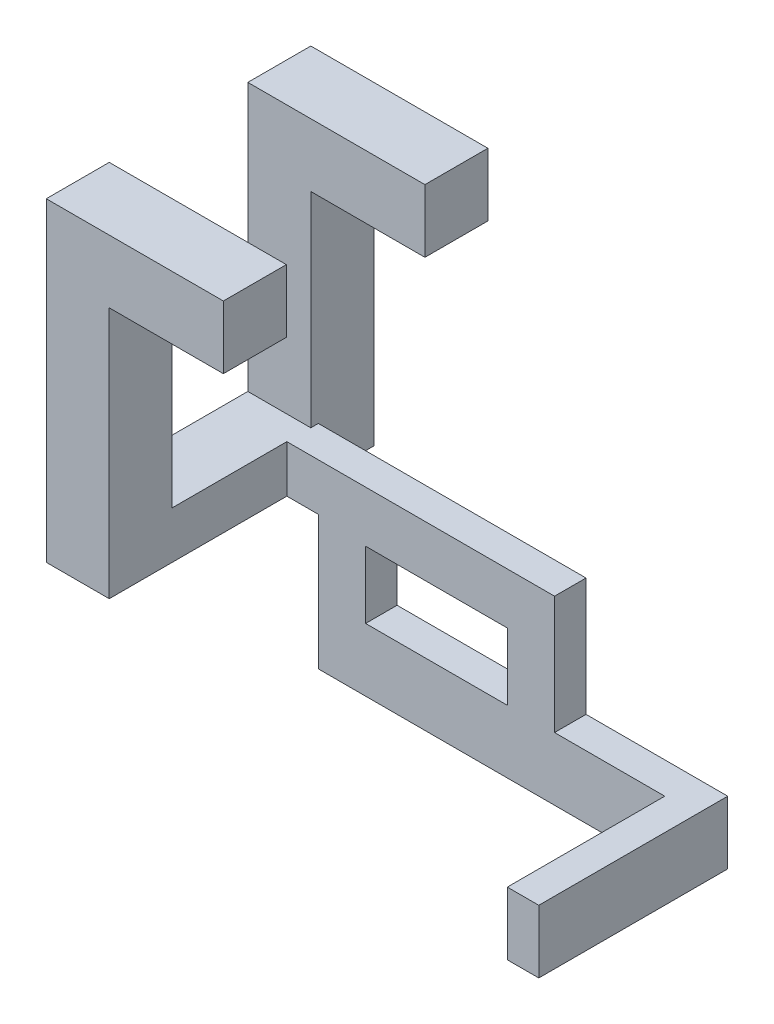
SolidWorks part; units mm, degrees
ref_plane "Front Plane" through (0, 0, 0) normal (0, 0, 1) x (1, 0, 0)
ref_plane "Top Plane" through (0, 0, 0) normal (0, 1, 0) x (1, 0, 0)
ref_plane "Right Plane" through (0, 0, 0) normal (1, 0, 0) x (0, 0, -1)
sketch "Sketch2" plane through (0, 0, 0) normal (0, 0, 1) x (1, 0, 0)
  line L1 (19.05, -14.605) -> (-19.05, -14.605)
  line L2 (19.05, -14.605) -> (19.05, 14.605)
  line L3 (19.05, 14.605) -> (-19.05, 14.605)
  line L4 (-19.05, -14.605) -> (-19.05, 14.605)
  line L5 (19.05, -14.605) -> (-19.05, 14.605) construction
  line L6 (19.05, 14.605) -> (-19.05, -14.605) construction
  point P0 (0, 0)
  dimension "D1" = 38.1
  dimension "D2" = 29.21
extrude "Boss-Extrude1" add sketch "Sketch2" along normal blind 5.08 contours L3 L4 L1 L2
sketch "Sketch3" plane through (0, 0, 5.08) normal (0, 0, 1) x (1, 0, 0)
  line L1 (-11.43, -6.35) -> (11.43, -6.35)
  line L2 (-11.43, -6.35) -> (-11.43, 6.35)
  line L3 (-11.43, 6.35) -> (11.43, 6.35)
  line L4 (11.43, -6.35) -> (11.43, 6.35)
  line L5 (-11.43, -6.35) -> (11.43, 6.35) construction
  line L6 (-11.43, 6.35) -> (11.43, -6.35) construction
  point P0 (0, 0)
  dimension "D1" = 22.86
  dimension "D2" = 12.7
extrude "Cut-Extrude1" cut sketch "Sketch3" against normal blind 5.08
sketch "Sketch5" plane through (-19.05, 0, 0) normal (-1, 0, 0) x (0, 0, 1)
  line L0 (0, -14.605) -> (0, 14.605) construction
  line L1 (5.08, 14.605) -> (0, 14.605)
  line L2 (5.08, 14.605) -> (5.08, 6.985)
  line L3 (5.08, 6.985) -> (0, 6.985)
  line L4 (0, 14.605) -> (0, 6.985)
  dimension "D1" = 7.62
extrude "Boss-Extrude2" add sketch "Sketch5" along normal blind 10.16
sketch "Sketch7" plane through (0, 0, 5.08) normal (0, 0, 1) x (1, 0, 0)
  line L0 (-29.21, 6.985) -> (-19.05, 6.985) construction
  line L1 (-29.21, 14.605) -> (-24.13, 14.605)
  line L2 (-29.21, 14.605) -> (-29.21, 6.985)
  line L3 (-29.21, 6.985) -> (-24.13, 6.985)
  line L4 (-24.13, 14.605) -> (-24.13, 6.985)
  dimension "D1" = 5.08
extrude "Boss-Extrude3" add sketch "Sketch7" along normal up to surface (18.49 mm away)
sketch "Sketch8" plane through (0, 6.985, 0) normal (0, -1, 0) x (1, 0, 0)
  line L1 (-24.13, 23.57) -> (-34.29, 23.57)
  line L2 (-24.13, 23.57) -> (-24.13, 33.73)
  line L3 (-24.13, 33.73) -> (-34.29, 33.73)
  line L4 (-34.29, 23.57) -> (-34.29, 33.73)
  line L5 (-24.13, 1.218) -> (-34.29, 1.218)
  line L6 (-24.13, 1.218) -> (-24.13, -8.942)
  line L7 (-24.13, -8.942) -> (-34.29, -8.942)
  line L8 (-34.29, 1.218) -> (-34.29, -8.942)
  dimension "D1" = 10.16
  dimension "D2" = 10.16
  dimension "D3" = 10.16
  dimension "D4" = 10.16
extrude "Boss-Extrude4" add sketch "Sketch8" against normal blind 50.8
sketch "Sketch9" plane through (-24.13, 0, 0) normal (1, 0, 0) x (0, 0, -1)
  line L0 (-23.57, 57.785) -> (-23.57, 14.605) construction
  line L1 (-33.73, 57.785) -> (-23.57, 57.785)
  line L2 (-33.73, 57.785) -> (-33.73, 47.625)
  line L3 (-33.73, 47.625) -> (-23.57, 47.625)
  line L4 (-23.57, 57.785) -> (-23.57, 47.625)
  line L5 (8.942, 57.785) -> (8.942, 6.985) construction
  line L6 (-1.218, 57.785) -> (8.942, 57.785)
  line L7 (-1.218, 57.785) -> (-1.218, 47.625)
  line L8 (-1.218, 47.625) -> (8.942, 47.625)
  line L9 (8.942, 57.785) -> (8.942, 47.625)
  dimension "D1" = 10.16
extrude "Boss-Extrude5" add sketch "Sketch9" along normal up to surface (18.4089 mm away)
sketch "Sketch11" plane through (19.05, 0, 0) normal (1, 0, 0) x (0, 0, -1)
  line L0 (-5.08, -14.605) -> (-5.08, 14.605) construction
  line L1 (-5.08, -4.445) -> (0, -4.445)
  line L2 (-5.08, -4.445) -> (-5.08, -14.605)
  line L3 (-5.08, -14.605) -> (0, -14.605)
  line L4 (0, -4.445) -> (0, -14.605)
  line L6 (-5.08, -14.605) -> (0, -14.605) construction
  dimension "D1" = 10.16
extrude "Boss-Extrude6" add sketch "Sketch11" along normal blind 22.86 and the other way up to surface
sketch "Sketch12" plane through (0, 0, 5.08) normal (0, 0, 1) x (1, 0, 0)
  line L0 (-19.05, -14.605) -> (41.91, -14.605) construction
  line L1 (41.91, -4.445) -> (36.83, -4.445)
  line L2 (41.91, -4.445) -> (41.91, -14.605)
  line L3 (41.91, -14.605) -> (36.83, -14.605)
  line L4 (36.83, -4.445) -> (36.83, -14.605)
  dimension "D1" = 5.08
extrude "Boss-Extrude7" add sketch "Sketch12" along normal blind 25.4
sketch "Sketch13" plane through (-29.21, 0, 0) normal (-1, 0, 0) x (0, 0, 1)
  line L1 (1.218, 6.985) -> (23.57, 6.985)
  line L2 (1.218, 6.985) -> (1.218, 14.605)
  line L3 (1.218, 14.605) -> (23.57, 14.605)
  line L4 (23.57, 6.985) -> (23.57, 14.605)
extrude "Boss-Extrude8" add sketch "Sketch13" along normal up to surface (5.08 mm away)
